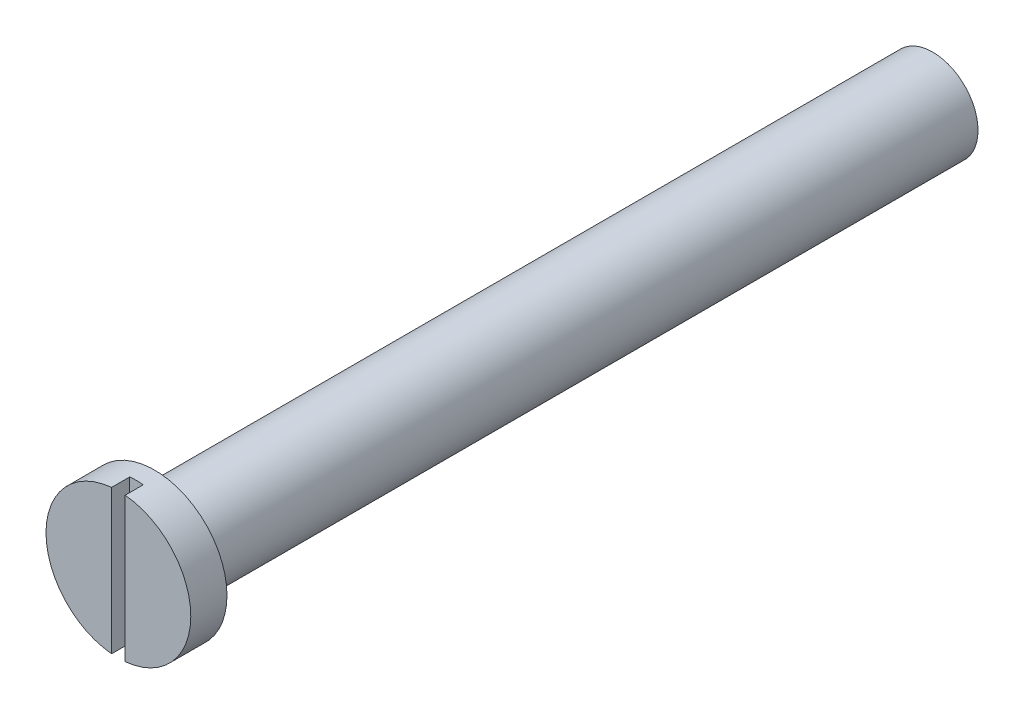
SolidWorks part; units mm, degrees
ref_plane "前视基准面" through (0, 0, 0) normal (0, 0, 1) x (1, 0, 0)
ref_plane "上视基准面" through (0, 0, 0) normal (0, 1, 0) x (1, 0, 0)
ref_plane "右视基准面" through (0, 0, 0) normal (1, 0, 0) x (0, 0, -1)
sketch "草图1" plane through (0, 0, 0) normal (0, 0, 1) x (1, 0, 0)
  circle A0 centre (0, 0) radius 5
  dimension "D1" = 10
extrude "凸台-拉伸1" add sketch "草图1" along normal blind 86
cosmetic thread "装饰螺纹线2" parameters "D1"=10, "D2"=4.134
sketch "草图2" plane through (0, 0, 86) normal (0, 0, 1) x (1, 0, 0)
  circle A0 centre (0, 0) radius 8
  dimension "D1" = 16
extrude "凸台-拉伸2" add sketch "草图2" along normal blind 4
sketch "草图4" plane through (0, 0, 90) normal (0, 0, 1) x (1, 0, 0)
  line L1 (-0.75, 9.78) -> (0.75, 9.78)
  line L2 (-0.75, 9.78) -> (-0.75, -9.78)
  line L3 (-0.75, -9.78) -> (0.75, -9.78)
  line L4 (0.75, 9.78) -> (0.75, -9.78)
  line L5 (-0.75, 9.78) -> (0.75, -9.78) construction
  line L6 (-0.75, -9.78) -> (0.75, 9.78) construction
  point P0 (0, 0)
  dimension "D1" = 1.5
extrude "切除-拉伸1" cut sketch "草图4" against normal blind 2
sketch "草图5" plane through (0, 0, 0) normal (0, 0, -1) x (-1, 0, 0)
  point P0 (0, 0)
  point P1 (-8.9921, 4.042)
hole_wizard "M8 螺纹孔的螺纹孔钻头1" positions "草图6" profile "草图8" hole size "M8" standard "GB"
sketch "草图6" plane through (0, 0, 0) normal (0, 0, -1) x (-1, 0, 0)
  point P0 (0, 0)
sketch "草图8" plane through (0, 0, 0) normal (1, 0, 0) x (0, 1, 0)
  line L0 (0, 0) -> (0, 17.0429)
  line L1 (0, 17.0429) -> (3.4, 15)
  line L2 (3.4, 15) -> (3.4, 0)
  line L5 (3.4, 0) -> (0, 0)
  line L10 (0, 17.0429) -> (-3.4, 15) construction
  line L11 (0, -6.35) -> (0, 107.95) construction
  dimension "孔直径" = 6.8
  dimension "孔深度" = 15
  dimension "导头角度" = 118
